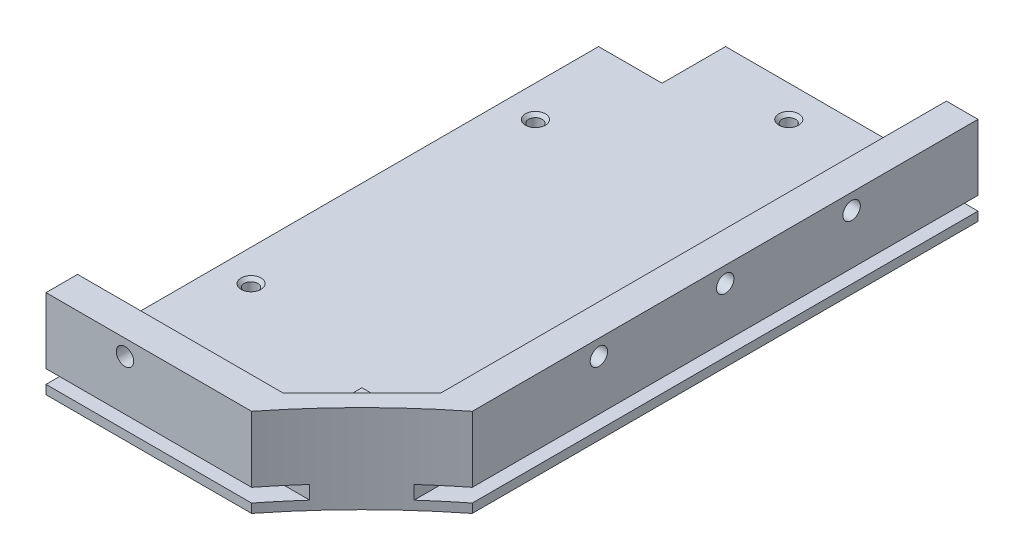
SolidWorks part; units mm, degrees
ref_plane "Front Plane" through (0, 0, 0) normal (0, 0, 1) x (1, 0, 0)
ref_plane "Top Plane" through (0, 0, 0) normal (0, 1, 0) x (1, 0, 0)
ref_plane "Right Plane" through (0, 0, 0) normal (1, 0, 0) x (0, 0, -1)
sketch "Sketch1" plane through (0, 0, 0) normal (0, 1, 0) x (1, 0, 0)
  line L0 (0, 0) -> (0, 650)
  line L1 (0, 650) -> (650, 650)
  line L2 (650, 650) -> (650, 0)
  line L3 (650, 0) -> (0, 0)
  dimension "D1" = 650
  dimension "D2" = 650
extrude "Boss-Extrude1" add sketch "Sketch1" along normal blind 8
sketch "Sketch3" plane through (0, 0, 0) normal (0, 0, 1) x (1, 0, 0)
  line L0 (325, 8) -> (325, 43.7071) construction
  line L1 (0, 8) -> (650, 8) construction
  line L2 (300, 43.7071) -> (350, 43.7071)
  line L3 (300, 43.7071) -> (265, 8)
  line L4 (265, 8) -> (385, 8)
  line L5 (385, 8) -> (350, 43.7071)
  point P7 (325, 43.7071)
  dimension "D1" = 50
  dimension "D2" = 50
  dimension "D3" = 50
  dimension "D4" = 120
extrude "Boss-Extrude2" add sketch "Sketch3" against normal blind 650
sketch "Sketch4" plane through (0, 0, 0) normal (0, 0, 1) x (1, 0, 0)
  line L0 (265, 8) -> (385, 8) construction
  circle A0 centre (325, 22) radius 11
  dimension "D1" = 14
extrude "Cut-Extrude2" cut sketch "Sketch4" against normal through all both and the other way through all
sketch "Sketch2" plane through (0, 8, 0) normal (0, 1, 0) x (1, 0, 0)
  line L0 (0, 650) -> (0, 0) construction
  line L1 (650, 650) -> (385, 650) construction
  circle A0 centre (325, 325) radius 210
  dimension "D3" = 420
  dimension "D1" = 325
  dimension "D2" = 325
extrude "Cut-Extrude1" cut sketch "Sketch2" against normal through all both and the other way through all
sketch "Sketch5" plane through (0, 0, 0) normal (0, 0, 1) x (1, 0, 0)
  line L0 (300, 43.7071) -> (350, 43.7071)
  line L1 (265, 8) -> (385, 8) construction
  line L2 (300, 8) -> (300, 28)
  line L3 (300, 8) -> (350, 8)
  line L4 (350, 8) -> (350, 28)
  line L5 (350, 28) -> (365.3961, 28)
  line L6 (385, 8) -> (350, 43.7071) construction
  line L7 (365.3961, 28) -> (350, 43.7071)
  line L8 (300, 28) -> (284.6039, 28)
  line L9 (300, 43.7071) -> (265, 8) construction
  line L10 (284.6039, 28) -> (300, 43.7071)
extrude "Cut-Extrude3" cut sketch "Sketch5" against normal blind 110 and the other way through all
sketch "Sketch6" plane through (0, 0, -650) normal (0, 0, -1) x (-1, 0, 0)
  line L0 (-265, 8) -> (-385, 8) construction
  line L1 (-350, 43.7071) -> (-300, 43.7071)
  line L2 (-300, 8) -> (-300, 28)
  line L3 (-300, 28) -> (-284.6039, 28)
  line L4 (-300, 43.7071) -> (-265, 8) construction
  line L5 (-284.6039, 28) -> (-300, 43.7071)
  line L6 (-350, 8) -> (-350, 28)
  line L7 (-350, 28) -> (-365.3961, 28)
  line L8 (-365.3961, 28) -> (-350, 43.7071)
  line L9 (-350, 8) -> (-300, 8)
extrude "Cut-Extrude4" cut sketch "Sketch6" against normal blind 110
sketch "Sketch7" plane through (0, 8, 0) normal (0, 1, 0) x (1, 0, 0)
  line L1 (325, 325) -> (325, 455) construction
  line L2 (325, 325) -> (325, 195) construction
  line L3 (325, 325) -> (455, 325) construction
  line L4 (325, 325) -> (195, 325) construction
  line L9 (325, 455) -> (455, 455) construction
  line L10 (455, 455) -> (455, 195) construction
  line L11 (455, 195) -> (195, 195) construction
  line L12 (195, 195) -> (195, 455) construction
  line L13 (195, 455) -> (325, 455) construction
  line L14 (195, 455) -> (195, 489.9242)
  line L15 (195, 489.9242) -> (195, 650)
  line L16 (265, 650) -> (0, 650) construction
  line L17 (195, 455) -> (160.0758, 455)
  line L18 (160.0758, 455) -> (0, 455)
  line L19 (0, 650) -> (0, 0) construction
  line L20 (0, 455) -> (-70.8389, 472.4621)
  line L21 (-70.8389, 472.4621) -> (-70.8389, 686.5445)
  line L22 (-70.8389, 686.5445) -> (167.4782, 686.5445)
  line L23 (167.4782, 686.5445) -> (195, 650)
  arc A0 (265, 526.2461) -> (265, 123.7539) centre (325, 325) ccw construction
  dimension "D1" = 130
  dimension "D2" = 130
  dimension "D3" = 130
  dimension "D4" = 130
extrude "Cut-Extrude5" cut sketch "Sketch7" against normal through all both and the other way through all flip side to cut
sketch "Sketch8" plane through (0, 0, -650) normal (0, 0, -1) x (-1, 0, 0)
  line L0 (-195, 8) -> (-195, 28)
  line L1 (-195, 28) -> (-185, 28)
  line L2 (-185, 28) -> (-185, 17)
  line L3 (-185, 17) -> (-175, 8)
  line L4 (-195, 8) -> (0, 8) construction
  line L5 (-175, 8) -> (-195, 8)
  dimension "D1" = 10
  dimension "D2" = 20
  dimension "D3" = 11
  dimension "D4" = 20
extrude "Boss-Extrude3" add sketch "Sketch8" against normal blind 160.08
sketch "Sketch10" plane through (0, 0, 0) normal (-1, 0, 0) x (0, 0, 1)
  line L0 (-455, 8) -> (-455, 28)
  line L1 (-455, 28) -> (-465, 28)
  line L2 (-465, 28) -> (-465, 17)
  line L3 (-465, 17) -> (-475, 8)
  line L4 (-650, 8) -> (-455, 8) construction
  line L5 (-475, 8) -> (-455, 8)
  dimension "D1" = 10
  dimension "D2" = 20
  dimension "D3" = 11
  dimension "D4" = 20
extrude "Boss-Extrude4" add sketch "Sketch10" against normal blind 160.08
sketch "Sketch21" plane through (0, 0, 0) normal (-1, 0, 0) x (0, 0, 1)
  line L0 (-455, 7.15) -> (-465, 7.15)
  line L1 (-455, 0) -> (-455, 28) construction
  line L2 (-465, 7.15) -> (-465, 2.85)
  line L3 (-465, 2.85) -> (-455, 2.85)
  line L4 (-455, 2.85) -> (-455, 7.15)
  line L5 (-650, 0) -> (-455, 0) construction
  dimension "D1" = 2.85
  dimension "D2" = 4.3
  dimension "D3" = 10
extrude "Cut-Extrude10" cut sketch "Sketch21" against normal through all
sketch "Sketch22" plane through (0, 0, -650) normal (0, 0, -1) x (-1, 0, 0)
  line L0 (-195, 7.15) -> (-185, 7.15)
  line L1 (-195, 0) -> (-195, 28) construction
  line L2 (-185, 7.15) -> (-185, 2.85)
  line L3 (-185, 2.85) -> (-195, 2.85)
  line L4 (-195, 2.85) -> (-195, 7.15)
  line L5 (-195, 0) -> (0, 0) construction
  dimension "D1" = 2.85
  dimension "D2" = 4.3
  dimension "D3" = 10
extrude "Cut-Extrude11" cut sketch "Sketch22" against normal through all
sketch "Sketch12" plane through (0, 8, 0) normal (0, 1, 0) x (1, 0, 0)
  line L0 (0, 0) -> (0, 650) construction
  line L1 (0, 650) -> (650, 650) construction
  line L2 (650, 650) -> (0, 0) construction
  circle A0 centre (325, 325) radius 210
sketch "Sketch23" plane through (0, 0, -489.92) normal (0, 0, 1) x (1, 0, 0)
  line L3 (194.9946, 8) -> (195, 28)
  line L4 (195, 28) -> (160.08, 28)
  line L5 (160.08, 28) -> (160.08, 8)
  line L6 (160.08, 8) -> (194.9946, 8)
extrude "Boss-Extrude5" add sketch "Sketch23" along normal blind 60
extrude "Cut-Extrude6" cut sketch "Sketch12" against normal through all both and the other way through all
sketch "Sketch26" plane through (0, 28, 0) normal (0, 1, 0) x (1, 0, 0)
  line L0 (185, 489.92) -> (160.08, 489.92)
  line L1 (160.08, 489.92) -> (160.08, 465)
  line L2 (160.08, 465) -> (185, 489.92)
extrude "Cut-Extrude14" cut sketch "Sketch26" against normal blind 11
sketch "Sketch27" plane through (185, 0, 0) normal (-1, 0, 0) x (0, 0, 1)
  line L0 (-650, 17) -> (-650, 28) construction
  line L1 (-489.92, 28) -> (-650, 28) construction
  circle A0 centre (-610, 23) radius 2.75
  circle A1 centre (-570, 23) radius 2.75
  circle A2 centre (-530, 23) radius 2.75
  dimension "D1" = 40
  dimension "D7" = 5.5
  dimension "D8" = 5.5
  dimension "D9" = 5.5
  dimension "D2" = 40
  dimension "D3" = 40
  dimension "D4" = 5
  dimension "D5" = 5
  dimension "D6" = 5
extrude "Cut-Extrude15" cut sketch "Sketch27" against normal blind 11
sketch "Sketch28" plane through (0, 0, -465) normal (0, 0, -1) x (-1, 0, 0)
  line L0 (0, 28) -> (0, 17) construction
  line L1 (-160.08, 28) -> (0, 28) construction
  circle A0 centre (-120, 23) radius 2.75
  circle A1 centre (-80, 23) radius 2.2
  circle A2 centre (-40, 23) radius 2.2
  dimension "D1" = 5.5
  dimension "D2" = 4.4
  dimension "D3" = 4.4
  dimension "D4" = 40
  dimension "D5" = 40
  dimension "D6" = 40
  dimension "D7" = 5
  dimension "D8" = 5
  dimension "D9" = 5
extrude "Cut-Extrude16" cut sketch "Sketch28" against normal blind 11
sketch "Sketch29" plane through (0, 8, 0) normal (0, 1, 0) x (1, 0, 0)
  line L0 (0, 650) -> (20, 650)
  line L1 (175, 650) -> (0, 650) construction
  line L2 (20, 650) -> (20, 630)
  line L3 (20, 630) -> (0, 630)
  line L4 (0, 650) -> (0, 475) construction
  line L5 (0, 630) -> (0, 650)
extrude "Cut-Extrude17" cut sketch "Sketch29" against normal blind 10
sketch "Sketch30" plane through (0, 8, 0) normal (0, 1, 0) x (1, 0, 0)
  line L6 (95, 650) -> (0, 650)
  line L7 (175, 650) -> (20, 650) construction
  line L8 (0, 650) -> (0, 455)
  line L9 (0, 630) -> (0, 475) construction
  line L10 (0, 455) -> (95, 455)
  line L11 (95, 650) -> (95, 455)
  dimension "D1" = 195
  dimension "D2" = 95
  dimension "D3" = 95
extrude "Cut-Extrude18" cut sketch "Sketch30" against normal through all both and the other way through all
sketch "Sketch31" plane through (0, 8, 0) normal (0, 1, 0) x (1, 0, 0)
  line L0 (95, 650) -> (115.1, 650)
  line L1 (175, 650) -> (95, 650) construction
  line L2 (115.1, 650) -> (115.1, 629.9)
  line L3 (115.1, 629.9) -> (95, 629.9)
  line L4 (95, 650) -> (95, 475) construction
  line L5 (95, 629.9) -> (95, 650)
  dimension "D1" = 20.1
  dimension "D2" = 20.1
extrude "Cut-Extrude19" cut sketch "Sketch31" against normal through all both and the other way through all
sketch "Sketch32" plane through (0, 8, 0) normal (0, 1, 0) x (1, 0, 0)
  line L0 (175, 650) -> (115.1, 650) construction
  line L1 (95, 629.9) -> (95, 475) construction
  line L2 (115.1, 650) -> (115.1, 629.9) construction
  line L3 (115.1, 629.9) -> (95, 629.9) construction
  circle A0 centre (105, 599.9) radius 2.15
  circle A1 centre (105, 509.9) radius 2.15
  circle A2 centre (145.1, 640) radius 2.15
  dimension "D1" = 4.3
  dimension "D2" = 4.3
  dimension "D3" = 4.3
  dimension "D4" = 10
  dimension "D5" = 10
  dimension "D6" = 10
  dimension "D7" = 30
  dimension "D8" = 30
  dimension "D9" = 90
extrude "Cut-Extrude20" cut sketch "Sketch32" against normal blind 10
chamfer "Chamfer1" distance 1 angle 45 3 edges at (105, 8, -507.75) (145.1, 8, -637.85) (105, 8, -597.75)
